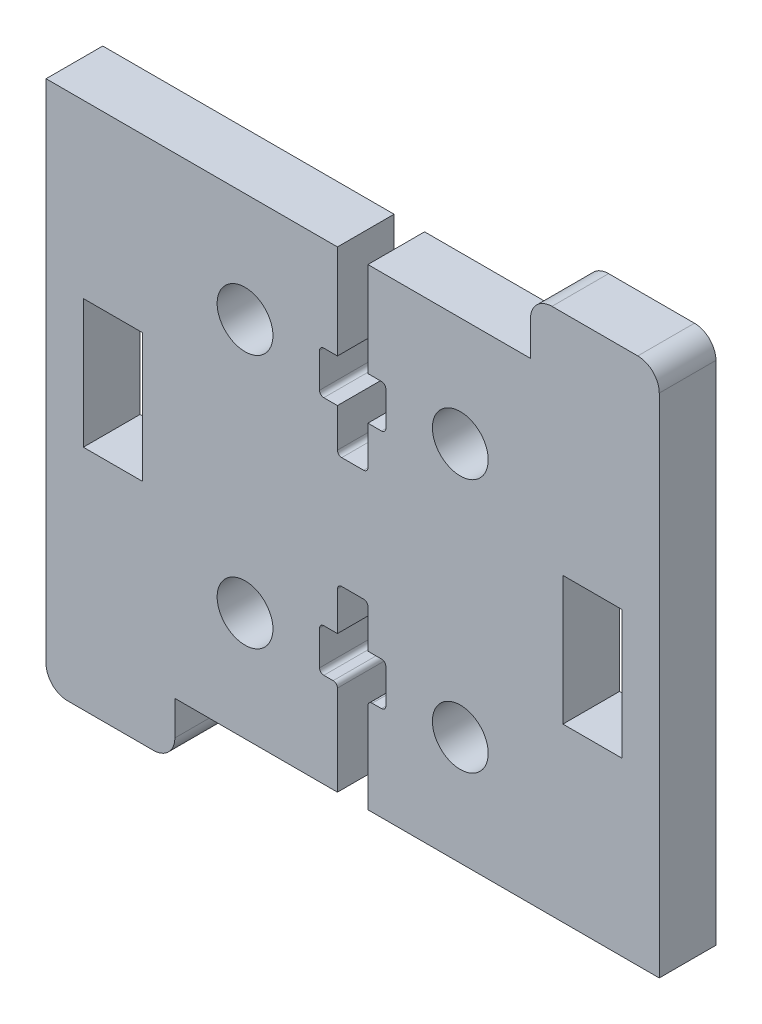
SolidWorks part; units mm, degrees
ref_plane "Front Plane" through (0, 0, 0) normal (0, 0, 1) x (1, 0, 0)
ref_plane "Top Plane" through (0, 0, 0) normal (0, 1, 0) x (1, 0, 0)
ref_plane "Right Plane" through (0, 0, 0) normal (1, 0, 0) x (0, 0, -1)
sketch "Model" plane through (0, 0, 0) normal (0, 0, 1) x (1, 0, 0)
  line L0 (4.34, 20) -> (4.34, 35)
  line L1 (11.22, 20) -> (4.34, 20)
  line L2 (11.22, 35) -> (11.22, 20)
  line L3 (4.34, 35) -> (11.22, 35)
  line L4 (67.08, 35) -> (67.08, 20)
  line L5 (60.2, 35) -> (67.08, 35)
  line L6 (60.2, 20) -> (60.2, 35)
  line L7 (67.08, 20) -> (60.2, 20)
  line L8 (39.57, 15.5) -> (39.57, 11.5)
  line L9 (37.485, 16) -> (39.07, 16)
  line L10 (37.485, 20.5) -> (37.485, 16)
  line L11 (34.435, 21) -> (36.985, 21)
  line L12 (33.935, 16) -> (33.935, 20.5)
  line L13 (32.35, 16) -> (33.935, 16)
  line L14 (31.85, 11.5) -> (31.85, 15.5)
  line L15 (33.435, 11) -> (32.35, 11)
  line L16 (33.935, 0) -> (33.935, 10.5)
  line L17 (2.5, -6.5) -> (12.5, -6.5)
  line L18 (0, 55) -> (0, -4)
  line L19 (33.935, 55) -> (0, 55)
  line L20 (33.935, 44) -> (33.935, 55)
  line L21 (32.35, 44) -> (33.935, 44)
  line L22 (31.85, 39.5) -> (31.85, 43.5)
  line L23 (33.935, 39) -> (32.35, 39)
  line L24 (33.935, 34.5) -> (33.935, 39)
  line L25 (36.985, 34) -> (34.435, 34)
  line L26 (37.485, 39) -> (37.485, 34.5)
  line L27 (39.07, 39) -> (37.485, 39)
  line L28 (39.57, 43.5) -> (39.57, 39.5)
  line L29 (37.485, 44) -> (39.07, 44)
  line L30 (37.485, 55) -> (37.485, 44)
  line L31 (68.92, 61.5) -> (58.92, 61.5)
  line L32 (71.42, 0) -> (71.42, 59)
  line L33 (37.485, 0) -> (71.42, 0)
  line L34 (37.485, 10.5) -> (37.485, 0)
  line L35 (39.07, 11) -> (37.985, 11)
  line L36 (56.42, 55) -> (37.485, 55)
  line L37 (15, -4) -> (15, 0)
  line L38 (56.42, 59) -> (56.42, 55)
  line L39 (15, 0) -> (33.935, 0)
  circle A0 centre (23.1748, 12.7) radius 3.25
  circle A1 centre (23.1748, 42.3) radius 3.25
  circle A2 centre (48.2452, 12.7) radius 3.25
  circle A3 centre (48.2452, 42.3) radius 3.25
  arc A4 (39.07, 11) -> (39.57, 11.5) centre (39.07, 11.5) ccw
  arc A5 (39.57, 15.5) -> (39.07, 16) centre (39.07, 15.5) ccw
  arc A6 (37.485, 20.5) -> (36.985, 21) centre (36.985, 20.5) ccw
  arc A7 (34.435, 21) -> (33.935, 20.5) centre (34.435, 20.5) ccw
  arc A8 (32.35, 16) -> (31.85, 15.5) centre (32.35, 15.5) ccw
  arc A9 (31.85, 11.5) -> (32.35, 11) centre (32.35, 11.5) ccw
  arc A10 (33.935, 10.5) -> (33.435, 11) centre (33.435, 10.5) ccw
  arc A11 (12.5, -6.5) -> (15, -4) centre (12.5, -4) ccw
  arc A12 (0, -4) -> (2.5, -6.5) centre (2.5, -4) ccw
  arc A13 (32.35, 44) -> (31.85, 43.5) centre (32.35, 43.5) ccw
  arc A14 (31.85, 39.5) -> (32.35, 39) centre (32.35, 39.5) ccw
  arc A15 (33.935, 34.5) -> (34.435, 34) centre (34.435, 34.5) ccw
  arc A16 (36.985, 34) -> (37.485, 34.5) centre (36.985, 34.5) ccw
  arc A17 (39.07, 39) -> (39.57, 39.5) centre (39.07, 39.5) ccw
  arc A18 (39.57, 43.5) -> (39.07, 44) centre (39.07, 43.5) ccw
  arc A19 (58.92, 61.5) -> (56.42, 59) centre (58.92, 59) ccw
  arc A20 (71.42, 59) -> (68.92, 61.5) centre (68.92, 59) ccw
  arc A21 (37.985, 11) -> (37.485, 10.5) centre (37.985, 10.5) ccw
extrude "Boss-Extrude1" add sketch "Model" along normal blind 6.6
